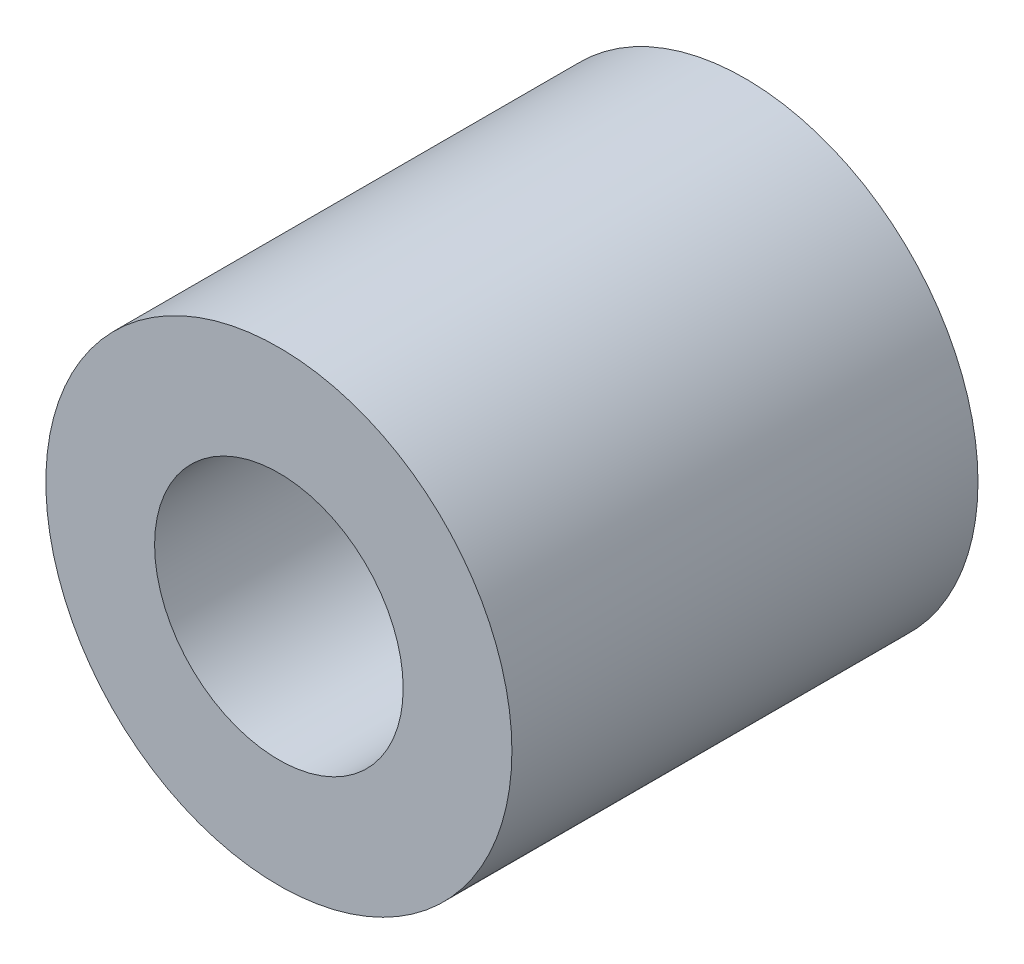
SolidWorks part; units mm, degrees
material "KS26"
ref_plane "正面" through (0, 0, 0) normal (0, 0, 1) x (1, 0, 0)
ref_plane "平面" through (0, 0, 0) normal (0, 1, 0) x (1, 0, 0)
ref_plane "右側面" through (0, 0, 0) normal (1, 0, 0) x (0, 0, -1)
sketch "ｽｹｯﾁ1" plane through (0, 0, 0) normal (0, 0, 1) x (1, 0, 0)
  circle A0 centre (0, 0) radius 3
  circle A1 centre (0, 0) radius 1.6
  dimension "D1" = 6
  dimension "D2" = 3.2
extrude "ﾎﾞｽ - 押し出し1" add sketch "ｽｹｯﾁ1" along normal mid plane 6
